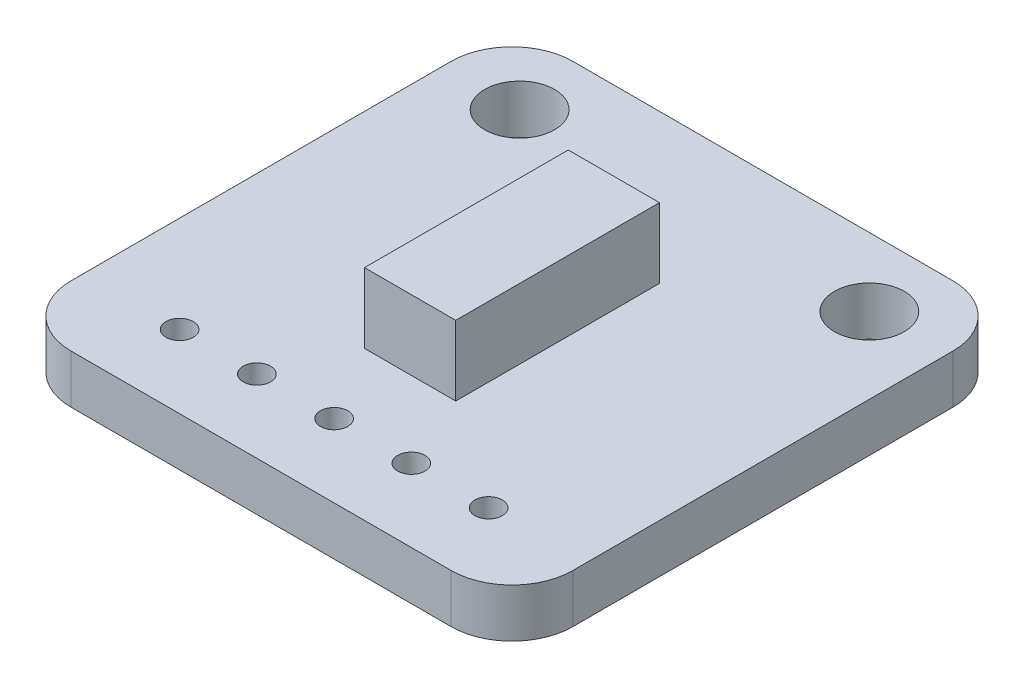
SolidWorks part; units mm, degrees
ref_plane "Front Plane" through (0, 0, 0) normal (0, 0, 1) x (1, 0, 0)
ref_plane "Top Plane" through (0, 0, 0) normal (0, 1, 0) x (1, 0, 0)
ref_plane "Right Plane" through (0, 0, 0) normal (1, 0, 0) x (0, 0, -1)
sketch "Sketch1" plane through (0, 0, 0) normal (0, 1, 0) x (1, 0, 0)
  line L1 (-8.25, -8.25) -> (8.25, -8.25)
  line L2 (-8.25, -8.25) -> (-8.25, 8.25)
  line L3 (-8.25, 8.25) -> (8.25, 8.25)
  line L4 (8.25, -8.25) -> (8.25, 8.25)
  line L5 (-8.25, -8.25) -> (8.25, 8.25) construction
  line L6 (-8.25, 8.25) -> (8.25, -8.25) construction
  line L7 (-5.75, -6) -> (5.75, -6) construction
  line L8 (-5.75, -6) -> (-5.75, 6) construction
  line L9 (-5.75, 6) -> (5.75, 6) construction
  line L10 (5.75, -6) -> (5.75, 6) construction
  line L11 (-5.75, -6) -> (5.75, 6) construction
  line L12 (-5.75, 6) -> (5.75, -6) construction
  circle A0 centre (-5.75, 6) radius 1.15
  circle A1 centre (5.75, 6) radius 1.15
  point P0 (0, 0)
  point P5 (0, 0)
  dimension "D1" = 2.3
  dimension "D2" = 11.5
  dimension "D3" = 16.5
  dimension "D4" = 1.1
extrude "Boss-Extrude1" add sketch "Sketch1" along normal blind 1.6
sketch "Sketch2" plane through (0, 1.6, 0) normal (0, 1, 0) x (1, 0, 0)
  line L1 (-1.5, -3.35) -> (1.5, -3.35)
  line L2 (-1.5, -3.35) -> (-1.5, 3.35)
  line L3 (-1.5, 3.35) -> (1.5, 3.35)
  line L4 (1.5, -3.35) -> (1.5, 3.35)
  line L5 (-1.5, -3.35) -> (1.5, 3.35) construction
  line L6 (-1.5, 3.35) -> (1.5, -3.35) construction
  point P0 (0, 0)
  dimension "D1" = 3
  dimension "D2" = 6.7
extrude "Boss-Extrude2" add sketch "Sketch2" along normal blind 2.3
sketch "Sketch4" plane through (0, 0, 0) normal (1, 0, 0) x (0, 0, -1)
  line L0 (-6.15, 0) -> (-6.15, -0.425)
  line L1 (-8.25, 0) -> (8.25, 0) construction
  line L2 (-6.65, -0.925) -> (-15.55, -0.925)
  line L3 (-15.55, -0.925) -> (-15.55, -1.525)
  line L4 (-15.55, -1.525) -> (-6.65, -1.525)
  line L5 (-5.55, -0.425) -> (-5.55, 0)
  line L6 (-5.55, 0) -> (-6.15, 0)
  line L7 (-15.55, -1.225) -> (-3.2477, -1.225) construction
  line L8 (-5.85, 0) -> (-5.85, 3.0457) construction
  line L9 (-8.25, 1.6) -> (-8.25, 0) construction
  arc A0 (-6.15, -0.425) -> (-6.65, -0.925) centre (-6.65, -0.425) cw
  arc A1 (-6.65, -1.525) -> (-5.55, -0.425) centre (-6.65, -0.425) ccw
  dimension "D1" = 0.6
  dimension "D5" = 0.5
  dimension "D2" = 10
  dimension "D3" = 1.225
  dimension "D4" = 2.4
extrude "Boss-Extrude4" add sketch "Sketch4" along normal blind 0.3 and the other way blind 0.3 separate body
pattern_linear "LPattern1" count 3 spacing 2.54 along (1, 0, 0) count 3 spacing 2.54 along (-1, 0, 0) of "Boss-Extrude4"
sketch "Sketch6" plane through (0, 1.6, 0) normal (0, 1, 0) x (1, 0, 0)
  line L0 (-5.38, -5.85) -> (-4.78, -5.85) construction
  line L1 (-5.38, -5.55) -> (-5.38, -6.15) construction
  line L2 (-4.78, -5.55) -> (-4.78, -6.15) construction
  line L3 (-2.84, -5.85) -> (-2.24, -5.85) construction
  line L4 (-2.84, -5.55) -> (-2.84, -6.15) construction
  line L5 (-2.24, -5.55) -> (-2.24, -6.15) construction
  line L6 (-0.3, -5.85) -> (0.3, -5.85) construction
  line L7 (-0.3, -5.55) -> (-0.3, -6.15) construction
  line L8 (0.3, -5.55) -> (0.3, -6.15) construction
  line L9 (2.24, -5.85) -> (2.84, -5.85) construction
  line L10 (2.24, -5.55) -> (2.24, -6.15) construction
  line L11 (2.84, -5.55) -> (2.84, -6.15) construction
  line L12 (4.78, -5.85) -> (5.38, -5.85) construction
  line L13 (4.78, -5.55) -> (4.78, -6.15) construction
  line L14 (5.38, -5.55) -> (5.38, -6.15) construction
  circle A0 centre (-5.08, -5.85) radius 0.45
  circle A1 centre (-2.54, -5.85) radius 0.45
  circle A2 centre (0, -5.85) radius 0.45
  circle A3 centre (2.54, -5.85) radius 0.45
  circle A4 centre (5.08, -5.85) radius 0.45
  dimension "D1" = 0.9
extrude "Cut-Extrude1" cut sketch "Sketch6" against normal through all
delete or keep bodies "Body-Delete/Keep 1" type delete bodies bodies 105 106 107 108 104
fillet "Fillet1" radius 2 4 edges at (8.25, 0.8, -8.25) (-8.25, 0.8, -8.25) (-8.25, 0.8, 8.25) (8.25, 0.8, 8.25)
